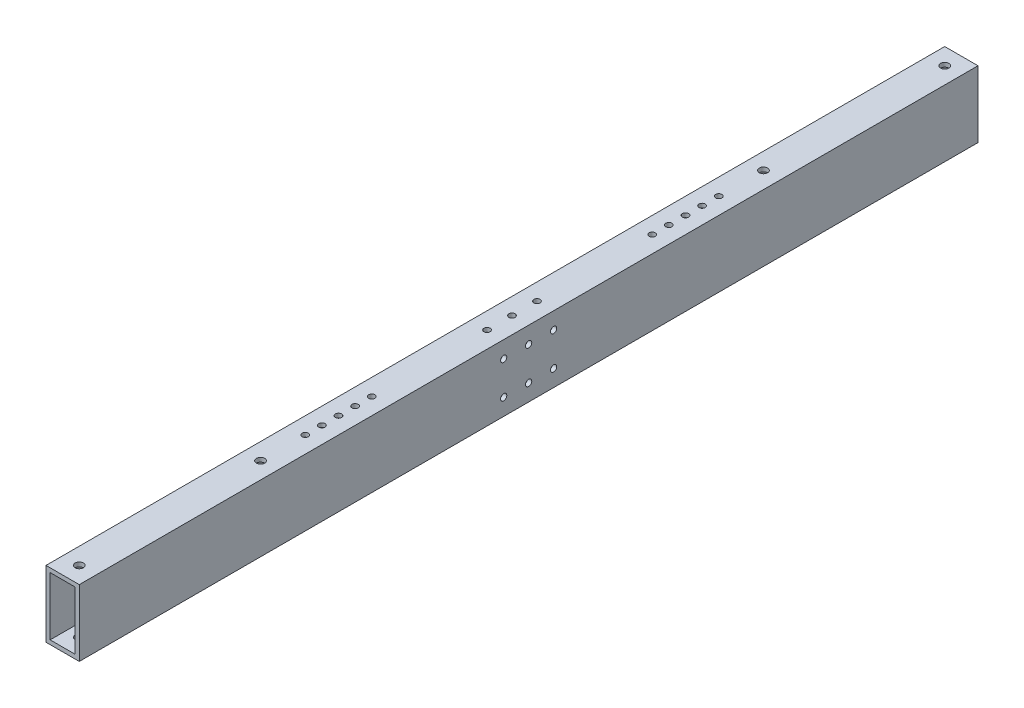
SolidWorks part; units mm, degrees
ref_plane "Front Plane" through (0, 0, 0) normal (0, 0, 1) x (1, 0, 0)
ref_plane "Top Plane" through (0, 0, 0) normal (0, 1, 0) x (1, 0, 0)
ref_plane "Right Plane" through (0, 0, 0) normal (1, 0, 0) x (0, 0, -1)
sketch "Sketch1" plane through (0, 0, 0) normal (0, 0, 1) x (1, 0, 0)
  line L0 (-9.525, 22.225) -> (9.525, 22.225)
  line L1 (-12.7, -25.4) -> (12.7, -25.4)
  line L2 (-12.7, -25.4) -> (-12.7, 25.4)
  line L3 (-12.7, 25.4) -> (12.7, 25.4)
  line L4 (12.7, -25.4) -> (12.7, 25.4)
  line L5 (-12.7, -25.4) -> (12.7, 25.4) construction
  line L6 (-12.7, 25.4) -> (12.7, -25.4) construction
  line L7 (9.525, -22.225) -> (9.525, 22.225)
  line L8 (-9.525, -22.225) -> (9.525, -22.225)
  line L9 (-9.525, -22.225) -> (-9.525, 22.225)
  point P0 (0, 0)
  dimension "D1" = 25.4
  dimension "D2" = 50.8
  dimension "D3" = 3.175
extrude "Boss-Extrude1" add sketch "Sketch1" along normal blind 685.8
sketch "Sketch2" plane through (0, 25.4, 0) normal (0, 1, 0) x (1, 0, 0)
  line L0 (0, -685.8) -> (0, 0) construction
  line L1 (12.7, -685.8) -> (-12.7, -685.8) construction
  line L2 (12.7, 0) -> (-12.7, 0) construction
  line L3 (-12.7, -342.9) -> (12.7, -342.9) construction
  line L4 (-12.7, -685.8) -> (-12.7, 0) construction
  line L5 (12.7, -685.8) -> (12.7, 0) construction
  circle A0 centre (0, -12.7) radius 3.175
  circle A1 centre (0, -151.0121) radius 3.175
  circle A2 centre (0, -534.7879) radius 3.175
  circle A3 centre (0, -673.1) radius 3.175
  circle A4 centre (0, -185.1063) radius 2.3812
  circle A5 centre (0, -197.8063) radius 2.3812
  circle A6 centre (0, -210.5063) radius 2.3812
  circle A7 centre (0, -223.2063) radius 2.3812
  circle A8 centre (0, -235.9063) radius 2.3812
  circle A9 centre (0, -449.8937) radius 2.3813
  circle A10 centre (0, -462.5937) radius 2.3813
  circle A11 centre (0, -475.2937) radius 2.3813
  circle A12 centre (0, -487.9937) radius 2.3813
  circle A13 centre (0, -500.6937) radius 2.3813
  dimension "D1" = 12.7
  dimension "D4" = 4.7625
  dimension "D3" = 138.3121
  dimension "D5" = 172.4063
  dimension "D2" = 2
  dimension "D6" = 5
extrude "Cut-Extrude1" cut sketch "Sketch2" against normal through all
sketch "Sketch3" plane through (12.7, 0, 0) normal (1, 0, 0) x (0, 0, -1)
  line L0 (-685.8, 0) -> (0, 0) construction
  line L1 (-685.8, -25.4) -> (-685.8, 25.4) construction
  line L2 (0, -25.4) -> (0, 25.4) construction
  line L3 (-342.9, 25.4) -> (-342.9, -25.4) construction
  line L4 (-685.8, 25.4) -> (0, 25.4) construction
  line L5 (-685.8, -25.4) -> (0, -25.4) construction
  line L6 (-361.95, -25.4) -> (-361.95, 25.4) construction
  circle A0 centre (-361.95, -12.7) radius 2.3813
  circle A1 centre (-342.9, -12.7) radius 2.3813
  circle A2 centre (-323.85, -12.7) radius 2.3813
  circle A3 centre (-323.85, 12.7) radius 2.3813
  circle A4 centre (-361.95, 12.7) radius 2.3813
  circle A5 centre (-342.9, 12.7) radius 2.3813
  dimension "D1" = 4.7625
  dimension "D4" = 4.7625
  dimension "D2" = 12.7
  dimension "D3" = 19.05
extrude "Cut-Extrude2" cut sketch "Sketch3" against normal blind 3.175
sketch "Sketch4" plane through (0, -25.4, 0) normal (0, -1, 0) x (-1, 0, 0)
  line L0 (0, -685.8) -> (0, 0) construction
  line L1 (12.7, -685.8) -> (-12.7, -685.8) construction
  line L2 (12.7, 0) -> (-12.7, 0) construction
  line L3 (-12.7, -342.9) -> (12.7, -342.9) construction
  line L4 (-12.7, -685.8) -> (-12.7, 0) construction
  line L5 (12.7, -685.8) -> (12.7, 0) construction
  circle A0 centre (0, -342.9) radius 2.3813
  circle A1 centre (0, -361.95) radius 2.3813
  circle A2 centre (0, -323.85) radius 2.3813
  dimension "D1" = 4.7625
  dimension "D2" = 4.7625
  dimension "D3" = 19.05
extrude "Cut-Extrude3" cut sketch "Sketch4" against normal through all
